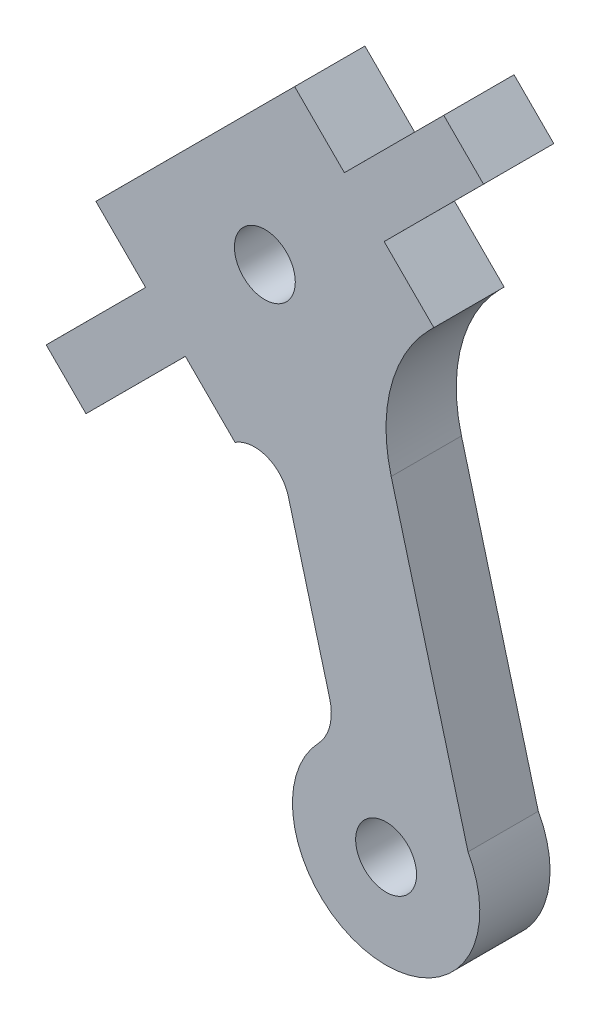
SolidWorks part; units mm, degrees
ref_plane "前视基准面" through (0, 0, 0) normal (0, 0, 1) x (1, 0, 0)
ref_plane "上视基准面" through (0, 0, 0) normal (0, 1, 0) x (1, 0, 0)
ref_plane "右视基准面" through (0, 0, 0) normal (1, 0, 0) x (0, 0, -1)
ref_plane "基准面1" through (0, 0, -3.3629) normal (0, 0, -1) x (-1, 0, 0)
sketch "草图1" plane through (0, 0, -3.3629) normal (0, 0, -1) x (-1, 0, 0)
  line L0 (-6.3042, 7.9338) -> (-4.5397, 14.5186)
  line L1 (-2.2643, 15.3821) -> (-0.1425, 17.5032)
  line L2 (-0.1425, 17.5032) -> (4.0998, 13.2597)
  line L3 (4.0998, 13.2597) -> (5.797, 14.9563)
  line L4 (5.797, 14.9563) -> (1.554, 19.2005)
  line L5 (1.554, 19.2005) -> (3.6758, 21.3217)
  line L6 (3.6758, 21.3217) -> (-4.8084, 29.8083)
  line L7 (-4.8084, 29.8083) -> (-6.932, 27.6854)
  line L8 (-6.932, 27.6854) -> (-11.1743, 31.929)
  line L9 (-11.1743, 31.929) -> (-12.8704, 30.2312)
  line L10 (-12.8704, 30.2312) -> (-8.6291, 25.9887)
  line L11 (-8.6291, 25.9887) -> (-10.7508, 23.8675)
  line L12 (-10.7508, 23.8675) -> (-10.6111, 23.7313)
  line L13 (-8.9295, 17.4533) -> (-12.2085, 5.2163)
  circle A0 centre (-8.7125, 3.275) radius 1.3
  arc A1 (-12.2085, 5.2163) -> (-5.8193, 6.0355) centre (-8.7125, 3.275) ccw
  arc A2 (-5.8193, 6.0355) -> (-6.3042, 7.9338) centre (-4.3723, 7.4162) cw
  arc A3 (-4.5397, 14.5186) -> (-2.2643, 15.3821) centre (-3.0908, 14.1303) cw
  arc A4 (-10.6111, 23.7313) -> (-8.9295, 17.4533) centre (-15.208, 19.1357) cw
  circle A5 centre (-3.5366, 22.594) radius 1.3
extrude "凸台-拉伸1" add sketch "草图1" against normal blind 3
